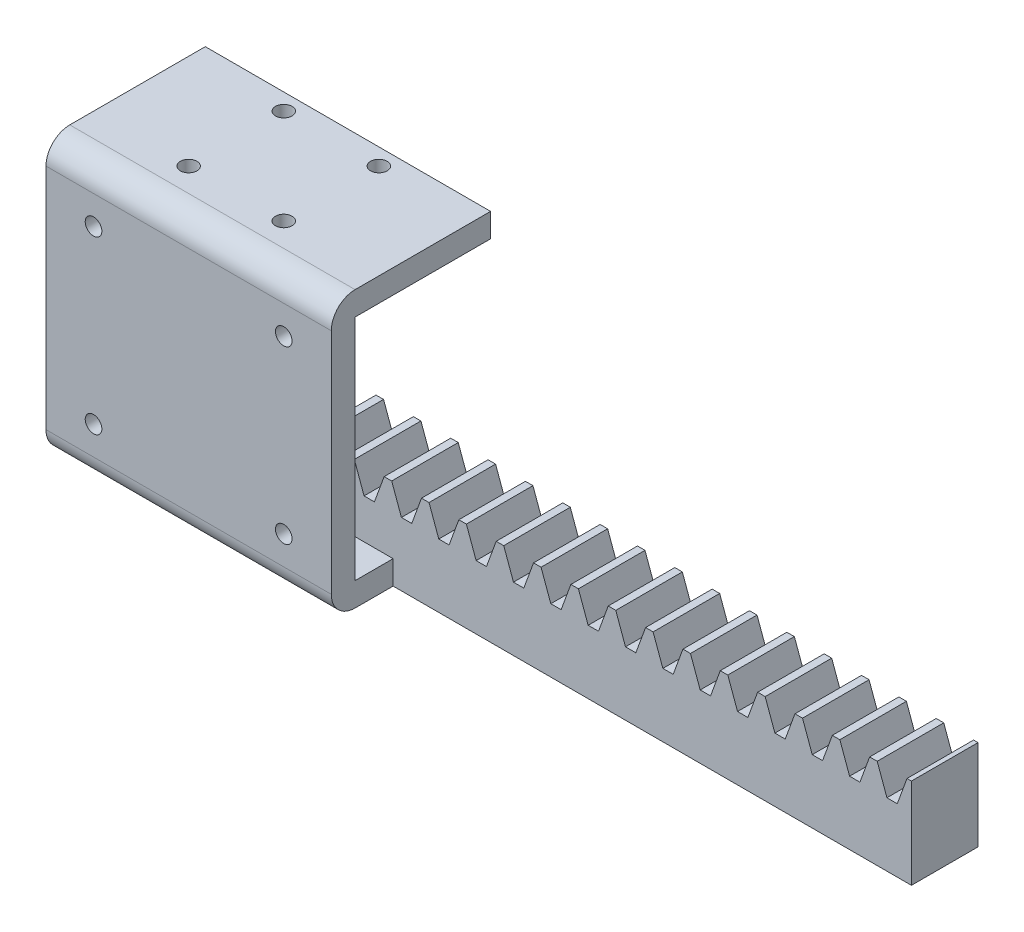
SolidWorks part; units mm, degrees
extrude "Blank" add sketch "BlankSke" against normal blind 14
sketch "BlankSke" plane through (0, 0, 0) normal (0, 0, 1) x (1, 0, 0)
  line L1 (0, 0) -> (209, 0)
  line L2 (0, 0) -> (0, 12.5)
  line L3 (0, 12.5) -> (209, 12.5)
  line L4 (209, 0) -> (209, 12.5)
  dimension "Length" = 209
  dimension "Blank_height" = 12.5
ref_plane "Plane1" through (0, 0, 0) normal (0, 0, 1) x (1, 0, 0)
ref_plane "Plane2" through (0, 0, 0) normal (0, 1, 0) x (1, 0, 0)
ref_plane "Plane3" through (0, 0, 0) normal (1, 0, 0) x (0, 0, -1)
other "Configuration Table"
sketch "HoldingSke" plane through (0, 0, 0) normal (0, 1, 0) x (1, 0, 0)
  line L0 (0, 0) -> (0.0557, 0.3961)
  line L1 (-15, 0) -> (100, 0) construction
  line L2 (0, 0) -> (-2.1039, 2.3779)
  line L3 (0, 0) -> (-11.863, 4.5341)
  line L4 (0, 0) -> (8.3015, 2.3804)
  line L5 (0, 0) -> (-23.7986, -8.8762)
  line L6 (0, 0) -> (-10.5278, -7.1032)
  line L9 (-71.009, 38.7566) -> (37.0557, 78.0889)
  line L10 (-76.2, 4.8779) -> (-66.2, 4.8779)
  line L11 (0, 0) -> (-5, 0)
  line L12 (-76.2, 101.6) -> (-76.113, 101.6)
  line L13 (24.9733, 27.94) -> (52.9518, 28.4284)
  line L14 (24.9733, 27.94) -> (24.9743, 27.94)
  line L15 (24.9733, 27.94) -> (100.4006, 29.5858)
  circle A0 centre (0, 0) radius 19.05
  circle A1 centre (0, 0) radius 5
  circle A2 centre (0, 0) radius 12.7
  dimension "MPH" = 10
  dimension "Diameter" = 38.1
  dimension "Num_teeth" = 16
  dimension "Pitch" = 0.4
  dimension "Show_teeth" = 998
  dimension "Thickness" = 12.7
  dimension "Ap" = 20
  dimension "Pitch_height" = 10
  dimension "Width" = 5
  dimension "Backlash" = 0.087
  dimension "Addendum_fac" = 1
  dimension "Dedendum_fac" = 1.25
  dimension "Clearance_fac" = 0.25
  dimension "Dedendum_add" = 0.001
  dimension "Length" = 115
  dimension "Module" = 2.5
sketch "TooCutSkeIll" plane through (0, 0, 0) normal (0, 0, 1) x (1, 0, 0)
  line L0 (-3.1105, 12.4342) -> (-1.237, 7.2869)
  line L1 (-0.6488, 6.875) -> (0.6488, 6.875)
  line L2 (1.237, 7.2869) -> (3.1105, 12.4342)
  line L3 (209, 12.5) -> (0, 12.5) construction
  line L4 (0, 0) -> (0, 64.897) construction
  line L5 (-13.208, 10) -> (12.954, 10) construction
  line L6 (0, 0) -> (209, 0) construction
  line L7 (2.2245, 10) -> (2.2245, 48.7463) construction
  line L8 (-2.2245, 10) -> (-2.2245, 48.7463) construction
  line L9 (3.2044, 12.5) -> (3.2044, 12.5254)
  line L10 (-3.2044, 12.5) -> (-3.2044, 12.5254)
  line L11 (-3.2044, 12.5254) -> (3.2044, 12.5254)
  arc A0 (0.6488, 6.875) -> (1.237, 7.2869) centre (0.6488, 7.501) ccw
  arc A1 (-1.237, 7.2869) -> (-0.6488, 6.875) centre (-0.6488, 7.501) ccw
  arc A2 (3.2044, 12.5) -> (3.1105, 12.4342) centre (3.2044, 12.4) ccw
  arc A3 (-3.1105, 12.4342) -> (-3.2044, 12.5) centre (-3.2044, 12.4) ccw
  dimension "Pitch_height" = 10
  dimension "Addendum_plus" = 2.5254
  dimension "Pressure_angle" = 20
  dimension "Gap_width" = 4.449
  dimension "Dedendum" = 3.125
extrude "ToothCutIll" cut sketch "TooCutSkeIll" against normal through all
sketch "TooCutSkeSim" plane through (0, 0, 0) normal (0, 0, 1) x (1, 0, 0)
  line L0 (1.0871, 6.875) -> (-1.0871, 6.875)
  line L1 (3.1437, 12.5254) -> (1.0871, 6.875)
  line L2 (0, 17.4625) -> (0, 53.467) construction
  line L3 (3.1437, 12.5254) -> (-3.1437, 12.5254)
  line L6 (-3.1437, 12.5254) -> (-1.0871, 6.875)
  line L9 (-2.2245, 10) -> (2.2245, 10) construction
  line L10 (0, 0) -> (209, 0) construction
  line L11 (2.2245, 10) -> (2.2245, 53.467) construction
  line L12 (-2.2245, 10) -> (-2.2245, 53.467) construction
  dimension "Pitch_height" = 10
  dimension "Addendum_plus" = 2.5254
  dimension "Pressure_angle" = 20
  dimension "Gap_width" = 4.449
  dimension "Dedendum" = 3.125
extrude "ToothCutSim" cut sketch "TooCutSkeSim" against normal through all
pattern_linear "TeethCuts" count 27 spacing 7.854 along (1, 0, 0) of "ToothCutSim"
sketch "Sketch8" plane through (0, 0, 0) normal (0, -1, 0) x (1, 0, 0)
  line L4 (209, 0) -> (0, 0)
  line L5 (0, 0) -> (0, -14)
  line L6 (0, -14) -> (209, -14)
  line L7 (209, -14) -> (209, 0)
  line L8 (209, 0) -> (0, 0)
  line L9 (0, 0) -> (0, -14)
  line L10 (0, -14) -> (209, -14)
  line L11 (209, -14) -> (209, 0)
  dimension "D1" = 0
extrude "Boss-Extrude3" add sketch "Sketch8" along normal blind 6.5
sketch "Sketch3" plane through (209, 0, 0) normal (1, 0, 0) x (0, 0, -1)
  line L0 (0, -6.5) -> (-13, -6.5) construction
  line L2 (-13, 22.5) -> (20.5, 22.5) construction
  line L3 (20.5, -6.5) -> (-13, -6.5)
  line L4 (0, 12.5) -> (0, -6.5)
  line L6 (14, -6.5) -> (14, 12.5)
  line L7 (14, 12.5) -> (0, 12.5)
  line L8 (0, 12.5) -> (0, -6.5) construction
  line L10 (14, -6.5) -> (14, 12.5) construction
  line L11 (14, 12.5) -> (0, 12.5) construction
  line L12 (20.5, -6.5) -> (20.5, -1.5)
  line L13 (20.5, 51.5) -> (-13, 51.5)
  line L14 (-13, -6.5) -> (-13, 51.5)
  line L15 (-8, 46.5) -> (-8, -1.5)
  line L16 (-8, -1.5) -> (20.5, -1.5)
  line L17 (20.5, -1.5) -> (20.5, 22.5) construction
  line L18 (20.5, 22.5) -> (20.5, 51.5) construction
  line L19 (-8, 46.5) -> (20.5, 46.5)
  line L20 (20.5, 46.5) -> (20.5, 51.5)
  line L24 (0, -6.5) -> (14, -6.5)
  line L26 (0, -6.5) -> (14, -6.5)
  circle A0 centre (-13, 4.5) radius 3 construction
  circle A1 centre (-13, 40.5) radius 3 construction
  point P21 (-8, 22.5)
  dimension "D5" = 18
  dimension "D6" = 6
  dimension "D2" = 13
  dimension "D3" = 6.5
  dimension "D4" = 29
  dimension "D7" = 5
  dimension "D8" = 5
  dimension "D1" = 0
extrude "Boss-Extrude1" add sketch "Sketch3" along normal blind 60 from surface at -209 contours L16 L12 L3 L14 L13 L20 L19 L15 starting at face at (0, 0.1875, -7)
sketch "Sketch4" plane through (0, 0, 13) normal (0, 0, 1) x (1, 0, 0)
  line L0 (30, 51.5) -> (30, -6.5) construction
  line L1 (60, 51.5) -> (0, 51.5) construction
  line L2 (60, -6.5) -> (0, -6.5) construction
  line L4 (10, 40.5) -> (50, 40.5) construction
  line L5 (10, 40.5) -> (10, 4.5) construction
  line L6 (10, 4.5) -> (50, 4.5) construction
  line L7 (50, 40.5) -> (50, 4.5) construction
  line L8 (10, 40.5) -> (50, 4.5) construction
  line L9 (10, 4.5) -> (50, 40.5) construction
  circle A0 centre (10, 40.5) radius 1.75
  circle A1 centre (50, 40.5) radius 1.75
  circle A2 centre (50, 4.5) radius 1.75
  circle A3 centre (10, 4.5) radius 1.75
  point P6 (30, 22.5)
  dimension "D3" = 3.5
  dimension "D1" = 40
  dimension "D2" = 36
extrude "Cut-Extrude1" cut sketch "Sketch4" against normal up to surface (5 mm away) up to face at (30, 22.5, 8)
sketch "Sketch6" plane through (0, -1.5, 0) normal (0, 1, 0) x (1, 0, 0)
  line L0 (30, -8) -> (30, 0) construction
  line L2 (0, 0) -> (60, 0) construction
  line L3 (40, -4) -> (20, -4) construction
  line L4 (60, -8) -> (0, -8) construction
  line L6 (43, -8) -> (17, -8)
  line L7 (43, -8) -> (43, 0)
  line L8 (43, 0) -> (17, 0)
  line L9 (17, -8) -> (17, 0)
  line L10 (43, -8) -> (17, 0) construction
  line L11 (43, 0) -> (17, -8) construction
  circle A0 centre (20, -4) radius 3 construction
  point P6 (30, -4)
  point P9 (30, -4)
  dimension "D2" = 6
  dimension "D1" = 10
extrude "Boss-Extrude2" add sketch "Sketch6" along normal up to surface (14 mm away) up to face at (19.635, 12.5, -7)
sketch "Sketch7" plane through (0, 12.5, 0) normal (0, 1, 0) x (1, 0, 0)
  line L0 (30, -8) -> (30, 20.5) construction
  line L1 (17, -8) -> (43, -8) construction
  line L2 (60, 20.5) -> (0, 20.5) construction
  line L3 (0, 14) -> (60, 14) construction
  line L4 (20, 17) -> (40, 17) construction
  line L5 (20, 17) -> (20, -3) construction
  line L6 (20, -3) -> (40, -3) construction
  line L7 (40, 17) -> (40, -3) construction
  line L8 (20, 17) -> (40, -3) construction
  line L9 (20, -3) -> (40, 17) construction
  circle A0 centre (20, 17) radius 1.75
  circle A1 centre (40, 17) radius 1.75
  circle A2 centre (40, -3) radius 1.75
  circle A3 centre (20, -3) radius 1.75
  point P6 (30, 7)
  dimension "D4" = 3.5
  dimension "D1" = 20
  dimension "D2" = 20
  dimension "D3" = 3
extrude "Cut-Extrude2" cut sketch "Sketch7" against normal through all both and the other way through all
fillet "Fillet1" radius 5 2 edges at (30, 51.5, 13) (30, -6.5, 13)
sketch "Sketch9" plane through (209, 0, 0) normal (1, 0, 0) x (0, 0, -1)
  line L4 (0, 12.5) -> (0, -6.5)
  line L5 (0, -6.5) -> (14, -6.5)
  line L6 (14, -6.5) -> (14, 12.5)
  line L7 (14, 12.5) -> (0, 12.5)
  line L8 (0, 12.5) -> (0, -6.5)
  line L9 (0, -6.5) -> (14, -6.5)
  line L10 (14, -6.5) -> (14, 12.5)
  line L11 (14, 12.5) -> (0, 12.5)
  dimension "D1" = 0
extrude "Cut-Extrude3" cut sketch "Sketch9" against normal blind 40
equation "' \"Module@HoldingSke\" = 6.35"
equation "' \"Num_teeth@HoldingSke\" = 12"
equation "' \"Ap@HoldingSke\" =  20"
equation "' \"Ap@HoldingSke\" = 20"
equation "' \"Width@HoldingSke\" = 0.25 * 25.4"
equation "' \"Show_teeth@HoldingSke\" = 500"
equation "' \"Backlash@HoldingSke\" = 0.009 * 25.4"
equation "' \"Addendum_fac@HoldingSke\" = 1.0"
equation "' \"Dedendum_fac@HoldingSke\" = 1.25"
equation "' \"Dedendum_add@HoldingSke\" = 0.00005 * 25.4"
equation "' \"Clearance_fac@HoldingSke\" = 0.25"
equation "' \"Pitch_height@HoldingSke\" = 1 * 25.4"
equation "' \"Length@HoldingSke\" = 4.71 * 25.4"
equation "\"Pitch@HoldingSke\" = 1 / \"Module@HoldingSke\""
equation "\"MPH@HoldingSke\" = \"Dedendum_fac@HoldingSke\" / \"Pitch@HoldingSke\" + 2 * \"Dedendum_add@HoldingSke\" + 0.002 * 25.4"
equation "\"MPH@HoldingSke\" = ((sgn( \"MPH@HoldingSke\" - \"Pitch_height@HoldingSke\")+1)*( \"MPH@HoldingSke\" - \"Pitch_height@HoldingSke\"))/2 + \"Pitch_height@HoldingSke\""
equation "\"Blank_height@BlankSke\" = \"Pitch_height@HoldingSke\" + \"Addendum_fac@HoldingSke\"  / \"Pitch@HoldingSke\" "
equation "\"Length@BlankSke\"=\"Length@HoldingSke\" +33mm+61mm"
equation "\"Pressure_angle@TooCutSkeIll\" = \"Ap@HoldingSke\""
equation "\"Addendum_plus@TooCutSkeIll\" =  \"Addendum_fac@HoldingSke\"  / \"Pitch@HoldingSke\" + 0.001 *25.4"
equation "\"Dedendum@TooCutSkeIll\" = \"Dedendum_fac@HoldingSke\"  / \"Pitch@HoldingSke\""
equation "\"Pitch_height@TooCutSkeIll\" =  \"MPH@HoldingSke\""
equation "\"Gap_width@TooCutSkeIll\" = 3.14159265 / 2 / \"Pitch@HoldingSke\" + 6 * \"Backlash@HoldingSke\""
equation "\"Pressure_angle@TooCutSkeSim\" = \"Ap@HoldingSke\""
equation "\"Addendum_plus@TooCutSkeSim\" =  \"Addendum_fac@HoldingSke\"  / \"Pitch@HoldingSke\" + 0.001 * 25.4"
equation "\"Dedendum@TooCutSkeSim\" = \"Dedendum_fac@HoldingSke\"  / \"Pitch@HoldingSke\""
equation "\"Pitch_height@TooCutSkeSim\" =  \"MPH@HoldingSke\""
equation "\"Gap_width@TooCutSkeSim\" = 3.14159265 / 2 / \"Pitch@HoldingSke\" + 6 * \"Backlash@HoldingSke\""
equation "\"Root_fillet@TooCutSkeIll\" = \"Clearance_fac@HoldingSke\" / \"Pitch@HoldingSke\" + \"Dedendum_add@HoldingSke\""
equation "\"Break_rad@TooCutSkeIll\" = 0.02 / \"Pitch@HoldingSke\" * 2"
equation "\"Linear_pitch@TeethCuts\" = 3.14159265 / \"Pitch@HoldingSke\""
equation "\"Num_teeth@HoldingSke\" = int( ( \"Length@HoldingSke\" + 0 ) / (3.14159265 / \"Pitch@HoldingSke\")) + 0.9999  + 1"
